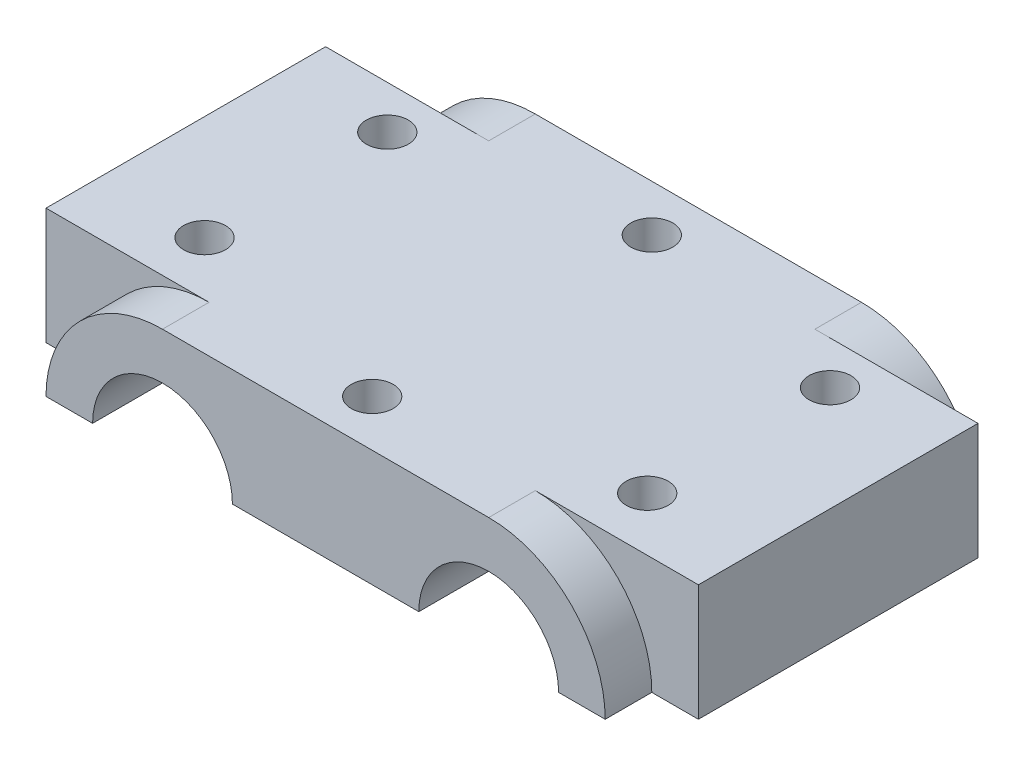
SolidWorks part; units mm, degrees
ref_plane "Front Plane" through (0, 0, 0) normal (0, 0, 1) x (1, 0, 0)
ref_plane "Top Plane" through (0, 0, 0) normal (0, 1, 0) x (1, 0, 0)
ref_plane "Right Plane" through (0, 0, 0) normal (1, 0, 0) x (0, 0, -1)
sketch "Sketch1" plane through (0, 0, 0) normal (0, 0, 1) x (1, 0, 0)
  line L1 (-35, 6.25) -> (35, 6.25)
  line L2 (-35, 6.25) -> (-35, -6.25)
  line L3 (-35, -6.25) -> (35, -6.25)
  line L4 (35, 6.25) -> (35, -6.25)
  point P0 (0, 0)
  dimension "D1" = 70
  dimension "D2" = 12.5
  dimension "D3" = 35
  dimension "D4" = 6.25
extrude "Boss-Extrude1" add sketch "Sketch1" against normal blind 30
sketch "Sketch2" plane through (0, 0, 0) normal (0, 0, 1) x (1, 0, 0)
  line L2 (-10, -6.25) -> (10, -6.25)
  line L3 (25, -6.25) -> (30, -6.25)
  line L4 (-35, -6.25) -> (35, -6.25) construction
  line L5 (-30, -6.25) -> (-25, -6.25)
  line L7 (-17.5, 6.25) -> (17.5, 6.25)
  arc A0 (-10, -6.25) -> (-25, -6.25) centre (-17.5, -6.25) ccw
  arc A1 (-17.5, 6.25) -> (-30, -6.25) centre (-17.5, -6.25) ccw
  arc A2 (25, -6.25) -> (10, -6.25) centre (17.5, -6.25) ccw
  arc A3 (30, -6.25) -> (17.5, 6.25) centre (17.5, -6.25) ccw
  dimension "D4" = 25
  dimension "D1" = 25
  dimension "D2" = 15
extrude "Boss-Extrude3" add sketch "Sketch2" along normal blind 5 and the other way blind 35 contours L7 A3 L3 A2 L2 A0 L5 A1
sketch "Sketch5" plane through (0, 0, 5) normal (0, 0, 1) x (1, 0, 0)
  line L0 (-25, -6.25) -> (-10, -6.25) construction
  line L1 (10, -6.25) -> (25, -6.25) construction
  line L2 (-25, -6.25) -> (-10, -6.25)
  line L3 (10, -6.25) -> (25, -6.25)
  arc A0 (-10, -6.25) -> (-25, -6.25) centre (-17.5, -6.25) ccw
  arc A1 (25, -6.25) -> (10, -6.25) centre (17.5, -6.25) ccw
extrude "Cut-Extrude1" cut sketch "Sketch5" against normal blind 66
sketch "Sketch7" plane through (0, 6.25, 0) normal (0, 1, 0) x (1, 0, 0)
  line L0 (17.5, 35) -> (17.5, 30) construction
  line L1 (-17.5, 35) -> (17.5, 35) construction
  line L4 (17.5, 0) -> (17.5, -5) construction
  circle A0 centre (0, 0) radius 2.25
  circle A1 centre (0, 30) radius 2.25
  circle A2 centre (23.75, 25.3721) radius 2.25
  circle A3 centre (23.75, 5.7594) radius 2.25
  circle A4 centre (-23.75, 25.3721) radius 2.25
  circle A5 centre (-23.75, 5.7594) radius 2.25
  dimension "D1" = 4.5
  dimension "D2" = 4.5
  dimension "D4" = 4.5
  dimension "D5" = 4.5
  dimension "D3" = 5
  dimension "D6" = 6.25
  dimension "D7" = 6.25
extrude "Cut-Extrude2" cut sketch "Sketch7" against normal blind 66
